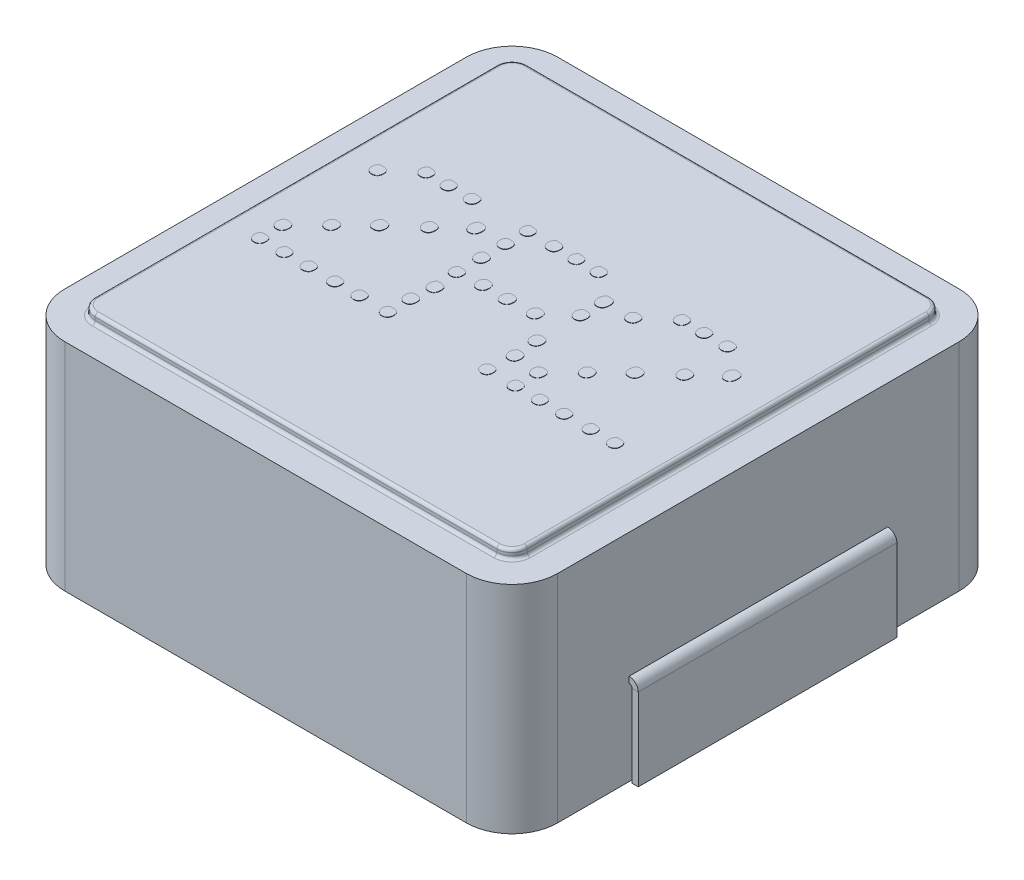
SolidWorks part; units mm, degrees
ref_plane "Front Plane" through (0, 0, 0) normal (0, 0, 1) x (1, 0, 0)
ref_plane "Top Plane" through (0, 0, 0) normal (0, 1, 0) x (1, 0, 0)
ref_plane "Right Plane" through (0, 0, 0) normal (1, 0, 0) x (0, 0, -1)
sketch "Sketch1" plane through (0, 0, 0) normal (0, 1, 0) x (1, 0, 0)
  line L1 (-1.6764, 2.0574) -> (1.6764, 2.0574)
  line L2 (-2.0574, 1.6764) -> (-2.0574, -1.6764)
  line L3 (-1.6764, -2.0574) -> (1.6764, -2.0574)
  line L4 (2.0574, 1.6764) -> (2.0574, -1.6764)
  arc A0 (-2.0574, 1.6764) -> (-1.6764, 2.0574) centre (-1.6764, 1.6764) cw
  arc A1 (1.6764, 2.0574) -> (2.0574, 1.6764) centre (1.6764, 1.6764) cw
  arc A2 (-2.0574, -1.6764) -> (-1.6764, -2.0574) centre (-1.6764, -1.6764) ccw
  arc A3 (1.6764, -2.0574) -> (2.0574, -1.6764) centre (1.6764, -1.6764) ccw
  point P0 (2.0574, 0)
  point P1 (0, 2.0574)
  dimension "D2" = 0.381
  dimension "D1" = 4.1148
extrude "Boss-Extrude1" add sketch "Sketch1" along normal blind 1.8796
sketch "Sketch3" plane through (0, 1.8796, 0) normal (0, 1, 0) x (1, 0, 0)
  line L0 (-1.6764, 1.8034) -> (1.6764, 1.8034)
  line L1 (-1.8034, 1.6764) -> (-1.8034, -1.6764)
  line L2 (-1.6764, -1.8034) -> (1.6764, -1.8034)
  line L3 (1.8034, -1.6764) -> (1.8034, 1.6764)
  line L4 (1.6764, 2.0574) -> (-1.6764, 2.0574) construction
  line L6 (-3.0734, 3.0734) -> (3.0734, 3.0734)
  line L7 (-3.0734, 3.0734) -> (-3.0734, -3.0734)
  line L8 (-3.0734, -3.0734) -> (3.0734, -3.0734)
  line L9 (3.0734, 3.0734) -> (3.0734, -3.0734)
  arc A0 (-1.8034, 1.6764) -> (-1.6764, 1.8034) centre (-1.6764, 1.6764) cw
  arc A1 (1.6764, 1.8034) -> (1.8034, 1.6764) centre (1.6764, 1.6764) cw
  arc A2 (-1.8034, -1.6764) -> (-1.6764, -1.8034) centre (-1.6764, -1.6764) ccw
  arc A3 (1.6764, -1.8034) -> (1.8034, -1.6764) centre (1.6764, -1.6764) ccw
  point P12 (3.0734, 0)
  point P14 (1.8034, 0)
  point P15 (0, 1.8034)
  point P16 (0, -3.0734)
  point P19 (0, -1.8034)
  dimension "D1" = 0.254
  dimension "D2" = 1.27
extrude "Cut-Extrude1" cut sketch "Sketch3" against normal blind 0.0762
sketch "Sketch4" plane through (2.0574, 0, 0) normal (1, 0, 0) x (0, 0, -1)
  line L0 (-1.6764, 0) -> (1.6764, 0) construction
  line L1 (-1.0795, 0.762) -> (1.0795, 0.762)
  line L2 (-1.0795, 0.762) -> (-1.0795, 0.7112)
  line L3 (-1.0795, 0.7112) -> (1.0795, 0.7112)
  line L4 (1.0795, 0.762) -> (1.0795, 0.7112)
  point P6 (0, 0)
  point P7 (0, 0.7112)
  dimension "D1" = 2.159
  dimension "D2" = 0.0508
  dimension "D3" = 0.762
sketch "Sketch5" plane through (0, 0, 0) normal (0, 0, 1) x (1, 0, 0)
  line L0 (2.0574, 0.7112) -> (2.0828, 0.7112) construction
  line L1 (2.0828, 0.7112) -> (2.0828, 0.6858) construction
  line L2 (2.0828, 0.6858) -> (2.0828, 0)
  line L3 (-1.6764, 0) -> (1.6764, 0) construction
  arc A0 (2.0574, 0.7112) -> (2.0828, 0.6858) centre (2.0574, 0.6858) cw
  dimension "D1" = 0.0254
sweep "Sweep1" add profiles "Sketch4" path "Sketch5"
mirror "Mirror1" about plane through (0, 0, 0) normal (1, 0, 0) of "Sweep1"
fillet "Fillet1" radius 0.0254 16 edges at (-1.7662, 1.8034, 1.7662) (-1.8034, 1.8034, 0) (-1.7662, 1.8034, -1.7662) (0, 1.8034, -1.8034) (1.7662, 1.8034, -1.7662) (1.8034, 1.8034, 0) (1.7662, 1.8034, 1.7662) (-1.7662, 1.8796, 1.7662) (-1.8034, 1.8796, 0) (-1.7662, 1.8796, -1.7662) (0, 1.8796, -1.8034) (1.7662, 1.8796, -1.7662) (1.8034, 1.8796, 0) (1.7662, 1.8796, 1.7662) (0, 1.8034, 1.8034) (0, 1.8796, 1.8034)
sketch "Sketch6" plane through (0, 1.8796, 0) normal (0, 1, 0) x (1, 0, 0)
  line L0 (-1.778, -0.6414) -> (1.778, -0.6414) construction
  line L1 (-1.778, 1.6764) -> (-1.778, -1.6764) construction
  line L2 (1.778, -1.6764) -> (1.778, 1.6764) construction
  text T0 "2R2" font "SF Telegraphic Light" height 1.27
extrude "Boss-Extrude2" add sketch "Sketch6" along normal blind 0.0025
